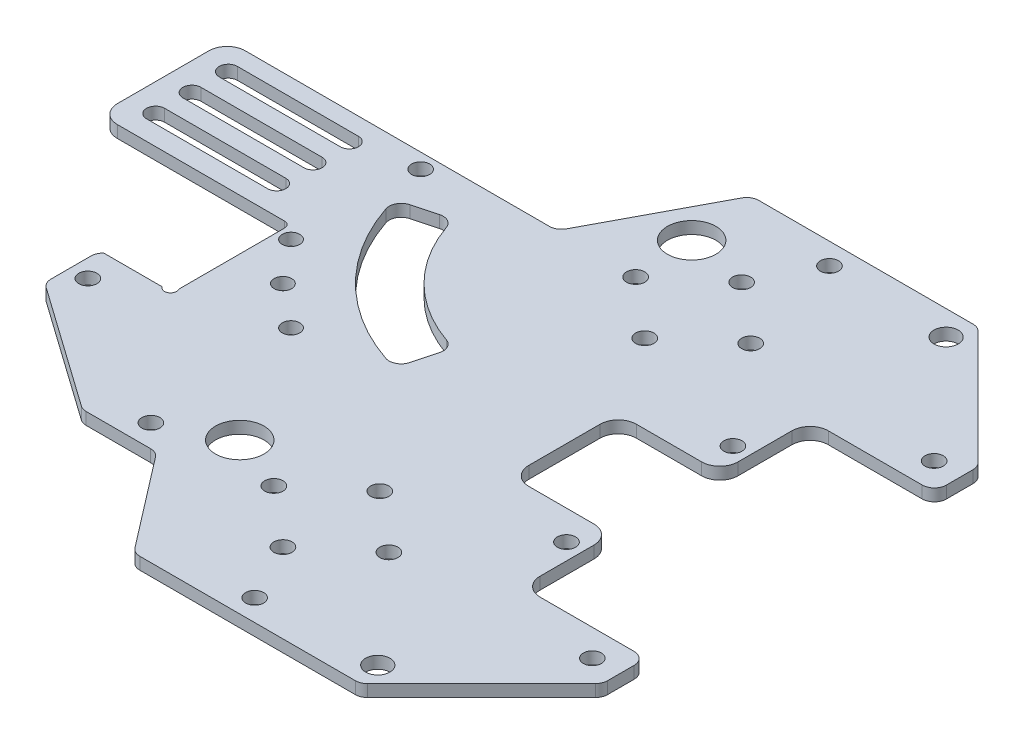
SolidWorks part; units mm, degrees
ref_plane "前视基准面" through (0, 0, 0) normal (0, 0, 1) x (1, 0, 0)
ref_plane "上视基准面" through (0, 0, 0) normal (0, 1, 0) x (1, 0, 0)
ref_plane "右视基准面" through (0, 0, 0) normal (1, 0, 0) x (0, 0, -1)
sketch "Sketch1" plane through (0, 0, 0) normal (0, 1, 0) x (1, 0, 0)
  line L0 (41.0899, -3.4167) -> (-33.1851, -3.4167) construction
  line L7 (54.8692, -12.3054) -> (44.0899, -12.3054)
  line L8 (41.0899, -9.3054) -> (41.0899, 2.4719)
  line L9 (44.0899, 5.4719) -> (54.8692, 5.4719)
  line L10 (57.8692, 8.4719) -> (57.8692, 17.3758)
  line L12 (-13.8687, 26.5833) -> (-44.6204, 26.5833)
  line L14 (-13.8687, 5.4719) -> (-44.6204, 5.4719)
  line L15 (-44.6204, 26.5833) -> (-44.6204, 5.4719)
  line L23 (16.5589, -4.4258) -> (17.5965, -0.5535)
  line L24 (-2.1519, 19.1949) -> (-6.0243, 18.1573)
  line L38 (20.9798, 47.5858) -> (9.813, 26.5833)
  line L39 (9.813, 26.5833) -> (-13.8687, 26.5833)
  line L40 (-13.8687, 5.4719) -> (-13.8687, -11.4447)
  line L41 (-13.8687, -11.4447) -> (-25.0098, -11.4447)
  line L42 (-25.0098, -11.4447) -> (-25.0098, -23.1435)
  line L43 (-25.0098, -23.1435) -> (-3.7966, -38.1435)
  line L44 (-3.7966, -38.1435) -> (8.4645, -38.1435)
  line L45 (8.4645, -38.1435) -> (20.9798, -54.4192)
  line L46 (20.9798, -54.4192) -> (58.3898, -54.4192)
  line L47 (58.3898, -54.4192) -> (78.3898, -34.4192)
  line L48 (78.3898, -34.4192) -> (78.3898, -27.2092)
  line L49 (78.3898, -27.2092) -> (60.8692, -27.2092)
  line L50 (57.8692, -24.2092) -> (57.8692, -15.3054)
  line L51 (60.8692, 20.3758) -> (78.3898, 20.3758)
  line L52 (78.3898, 20.3758) -> (78.3898, 27.5858)
  line L53 (78.3898, 27.5858) -> (58.3898, 47.5858)
  line L54 (58.3898, 47.5858) -> (20.9798, 47.5858)
  arc A4 (57.8692, -24.2092) -> (60.8692, -27.2092) centre (60.8692, -24.2092) ccw
  arc A5 (60.8692, 20.3758) -> (57.8692, 17.3758) centre (60.8692, 17.3758) ccw
  arc A6 (57.8692, -15.3054) -> (54.8692, -12.3054) centre (54.8692, -15.3054) ccw
  arc A7 (41.0899, -9.3054) -> (44.0899, -12.3054) centre (44.0899, -9.3054) ccw
  arc A8 (44.0899, 5.4719) -> (41.0899, 2.4719) centre (44.0899, 2.4719) ccw
  arc A9 (54.8692, 5.4719) -> (57.8692, 8.4719) centre (54.8692, 8.4719) ccw
  circle A10 centre (32.4798, -41.2942) radius 1.5
  circle A11 centre (41.9798, -33.2942) radius 1.5
  circle A12 centre (32.4798, -25.2942) radius 1.5
  circle A13 centre (22.9798, -33.2942) radius 1.5
  arc A17 (13.9897, -5.8039) -> (16.5589, -4.4258) centre (14.6271, -3.9082) ccw
  arc A18 (17.5965, -0.5535) -> (16.319, 1.8541) centre (15.6647, -0.0358) ccw
  arc A19 (0.2557, 17.9174) -> (-2.1519, 19.1949) centre (-1.6343, 17.2631) ccw
  arc A20 (0.2557, 17.9174) -> (16.319, 1.8541) centre (24.8249, 26.4234) ccw
  arc A21 (-6.0243, 18.1573) -> (-7.4024, 15.5881) centre (-5.5066, 16.2255) ccw
  arc A22 (-7.4024, 15.5881) -> (13.9897, -5.8039) centre (24.8249, 26.4234) ccw
  circle A23 centre (-10.1941, 24.1202) radius 1.5
  circle A24 centre (-22.0497, -18.9846) radius 1.5
  circle A25 centre (3.7985, -34.4192) radius 1.5
  circle A26 centre (57.1939, -50.3459) radius 2
  circle A27 centre (55.1743, -17.1595) radius 1.5
  circle A28 centre (55.1743, 10.3261) radius 1.5
  circle A35 centre (-10.8665, 3.389) radius 1.45
  circle A36 centre (-5.2086, -3.6102) radius 1.45
  circle A37 centre (1.7906, -9.268) radius 1.45
  circle A38 centre (57.1939, 43.5124) radius 2
  circle A39 centre (22.9798, 26.4608) radius 1.5
  circle A40 centre (32.4798, 18.4608) radius 1.5
  circle A41 centre (41.9798, 26.4608) radius 1.5
  circle A42 centre (32.4798, 34.4608) radius 1.5
extrude "Boss-Extrude1" add sketch "Sketch1" along normal blind 2
sketch "Sketch2" plane through (0, 0, 0) normal (0, -1, 0) x (1, 0, 0)
  line L0 (-40.0419, -10.2002) -> (-20.0419, -10.2002) construction
  line L1 (-40.0419, -8.7002) -> (-20.0419, -8.7002)
  line L2 (-40.0419, -11.7002) -> (-20.0419, -11.7002)
  line L3 (-40.0419, -17.7002) -> (-20.0419, -17.7002)
  line L6 (-40.0419, -14.7002) -> (-20.0419, -14.7002)
  line L7 (-40.0419, -16.2002) -> (-20.0419, -16.2002) construction
  line L8 (-40.0419, -23.7002) -> (-20.0419, -23.7002)
  line L9 (-40.0419, -20.7002) -> (-20.0419, -20.7002)
  line L10 (-40.0419, -22.2002) -> (-20.0419, -22.2002) construction
  arc A0 (-40.0419, -8.7002) -> (-40.0419, -11.7002) centre (-40.0419, -10.2002) ccw
  arc A1 (-20.0419, -11.7002) -> (-20.0419, -8.7002) centre (-20.0419, -10.2002) ccw
  arc A4 (-40.0419, -14.7002) -> (-40.0419, -17.7002) centre (-40.0419, -16.2002) ccw
  arc A5 (-20.0419, -17.7002) -> (-20.0419, -14.7002) centre (-20.0419, -16.2002) ccw
  arc A6 (-40.0419, -20.7002) -> (-40.0419, -23.7002) centre (-40.0419, -22.2002) ccw
  arc A7 (-20.0419, -23.7002) -> (-20.0419, -20.7002) centre (-20.0419, -22.2002) ccw
  point P2 (-30.0419, -10.2002)
  point P11 (-30.0419, -16.2002)
  point P18 (-30.0419, -22.2002)
  dimension "D1" = 3
extrude "Cut-Extrude1" cut sketch "Sketch2" against normal blind 2
fillet "Fillet1" radius 3 2 edges at (-44.6204, 1, -5.4719) (-44.6204, 1, -26.5833)
sketch "Sketch3" plane through (0, 0, 0) normal (0, -1, 0) x (1, 0, 0)
  circle A4 centre (37.3949, -44.0491) radius 1.5
  circle A5 centre (37.3949, 50.8826) radius 1.5
  circle A6 centre (73.9274, 31.6377) radius 1.5
  circle A7 centre (73.9274, -24.8042) radius 1.5
extrude "Cut-Extrude2" cut sketch "Sketch3" against normal blind 10
sketch "草图1" plane through (0, 0, 0) normal (0, -1, 0) x (1, 0, 0)
  line L0 (-13.8687, 11.4447) -> (-25.0098, 11.4447) construction
  line L1 (-13.8687, 11.4447) -> (-25.0098, 11.4447)
  line L2 (-13.8687, 11.4447) -> (-13.8687, 13.5087)
  line L3 (-13.8687, 13.5087) -> (-25.0098, 13.5087)
  line L4 (-25.0098, 11.4447) -> (-25.0098, 13.5087)
  line L5 (-13.8687, -5.4719) -> (-13.8687, 11.4447) construction
  line L6 (-25.0098, 11.4447) -> (-25.0098, 23.1435) construction
extrude "切除-拉伸1" cut sketch "草图1" against normal blind 10
sketch "草图2" plane through (0, 0, 0) normal (0, -1, 0) x (1, 0, 0)
  line L3 (41.0899, 3.4167) -> (40.3774, 3.4167) construction
  circle A4 centre (13.6015, 29.5432) radius 4
  circle A5 centre (22.3516, -36.3362) radius 4
extrude "切除-拉伸2" cut sketch "草图2" against normal through all
fillet "Fillet2" radius 2 14 edges at (78.3898, 1, -20.3758) (78.3898, 1, -27.5858) (58.3898, 1, -47.5858) (20.9798, 1, -47.5858) (9.813, 1, -26.5833) (78.3898, 1, 34.4192) (78.3898, 1, 27.2092) (58.3898, 1, 54.4192) (20.9798, 1, 54.4192) (8.4645, 1, 38.1435) (-3.7966, 1, 38.1435) (-25.0098, 1, 23.1435) (-25.0098, 1, 13.5087) (-13.8687, 1, -5.4719)
sketch "Sketch4" plane through (0, 2, 0) normal (0, 1, 0) x (1, 0, 0)
  circle A0 centre (-13.8687, -13.5087) radius 1
extrude "Cut-Extrude3" cut sketch "Sketch4" against normal blind 10
sketch "Sketch5" plane through (0, 2, 0) normal (0, 1, 0) x (1, 0, 0)
  line L0 (-41.6204, 5.4719) -> (-15.8687, 5.4719) construction
  line L1 (-24.8426, 5.4719) -> (-13.0152, 5.4719)
  line L2 (-24.8426, 5.4719) -> (-24.8426, -14.0311)
  line L3 (-24.8426, -14.0311) -> (-13.0152, -14.0311)
  line L4 (-13.0152, 5.4719) -> (-13.0152, -14.0311)
extrude "Cut-Extrude4" cut sketch "Sketch5" against normal blind 10
fillet "Fillet3" radius 1 1 edges at (-13.0152, 1, -5.4719)
